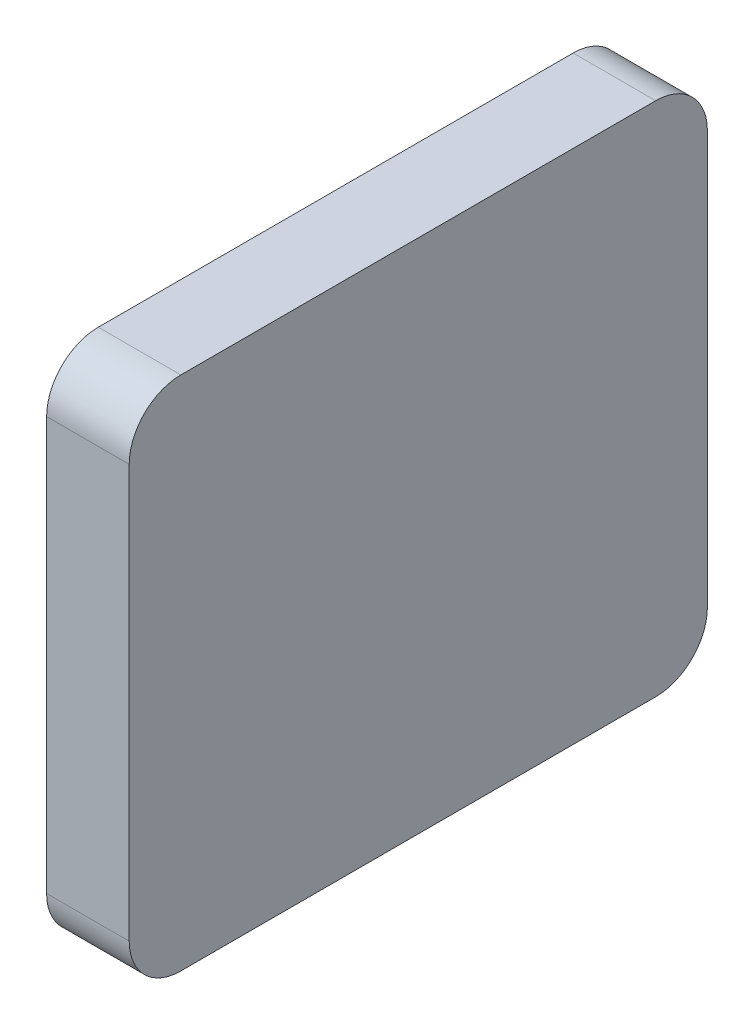
SolidWorks part; units mm, degrees
material "Chrome Stainless Steel"
ref_plane "Front Plane" through (0, 0, 0) normal (0, 0, 1) x (1, 0, 0)
ref_plane "Top Plane" through (0, 0, 0) normal (0, 1, 0) x (1, 0, 0)
ref_plane "Right Plane" through (0, 0, 0) normal (1, 0, 0) x (0, 0, -1)
sketch "BaseS" plane through (0, 0, 0) normal (1, 0, 0) x (0, 0, -1)
  line L1 (-2.8, 2.5) -> (2.8, 2.5)
  line L2 (-2.8, 2.5) -> (-2.8, -2.5)
  line L3 (-2.8, -2.5) -> (2.8, -2.5)
  line L4 (2.8, 2.5) -> (2.8, -2.5)
  line L5 (-2.8, 2.5) -> (2.8, -2.5) construction
  line L6 (-2.8, -2.5) -> (2.8, 2.5) construction
  point P0 (0, 0)
  dimension "Length" = 5.6
  dimension "Width" = 5
extrude "Base" add sketch "BaseS" along normal mid plane 0.8
fillet "BaseF" radius 0.5 4 edges at (0, -2.5, -2.8) (0, -2.5, 2.8) (0, 2.5, 2.8) (0, 2.5, -2.8)
